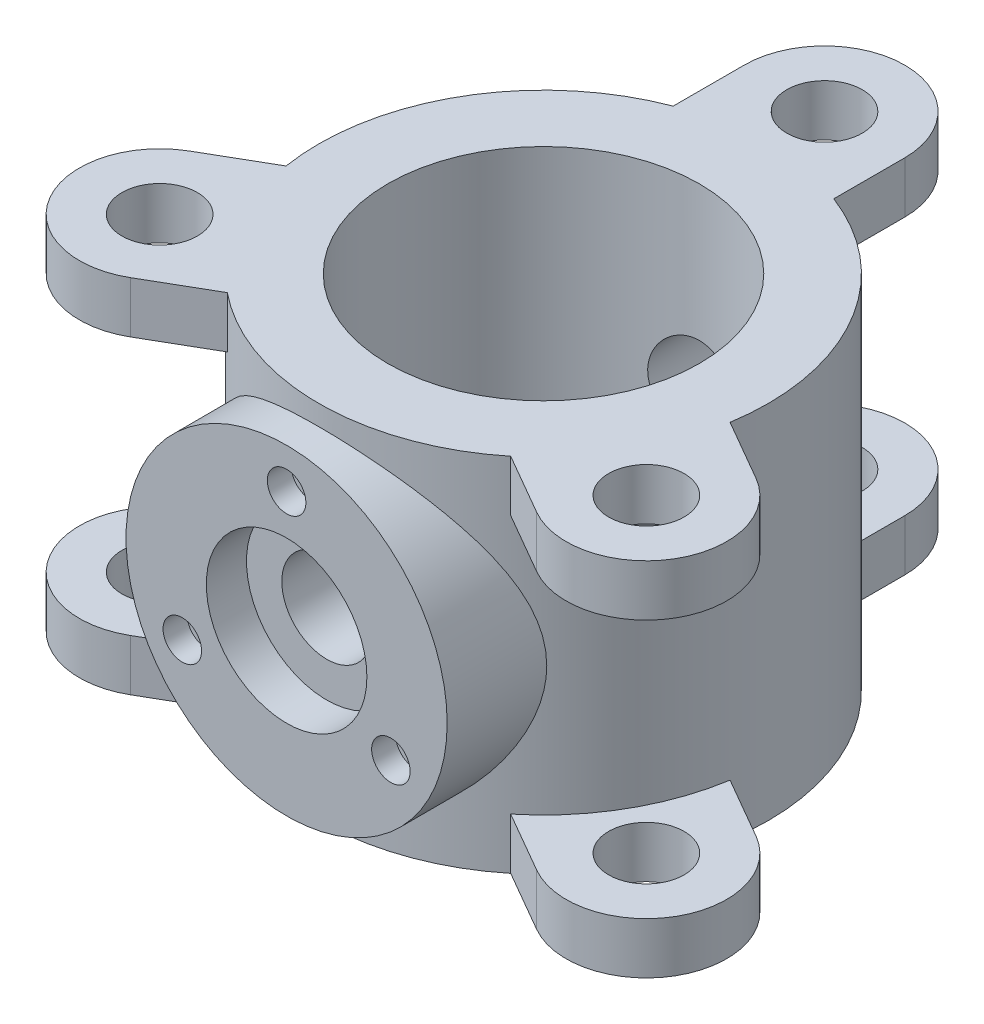
SolidWorks part; units mm, degrees
ref_plane "Front Plane" through (0, 0, 0) normal (0, 0, 1) x (1, 0, 0)
ref_plane "Top Plane" through (0, 0, 0) normal (0, 1, 0) x (1, 0, 0)
ref_plane "Right Plane" through (0, 0, 0) normal (1, 0, 0) x (0, 0, -1)
sketch "Sketch1" plane through (0, 0, 0) normal (0, 1, 0) x (1, 0, 0)
  circle A0 centre (0, 0) radius 140
  circle A1 centre (0, 0) radius 97
  dimension "D1" = 194
  dimension "D2" = 280
extrude "Boss-Extrude1" add sketch "Sketch1" along normal blind 225
sketch "Sketch3" plane through (0, 225, 0) normal (0, 1, 0) x (1, 0, 0)
  line L1 (50, 175) -> (-50, 175) construction
  line L2 (50, 175) -> (50, 101.9872)
  line L3 (50, 101.9872) -> (-50, 101.9872)
  line L4 (-50, 175) -> (-50, 101.9872)
  line L5 (50, 175) -> (-50, 101.9872) construction
  line L6 (50, 101.9872) -> (-50, 175) construction
  arc A0 (50, 175) -> (-50, 175) centre (0, 175) ccw
  circle A1 centre (0, 175) radius 23.5
  point P0 (0, 138.4936)
  dimension "D1" = 175
  dimension "D2" = 100
  dimension "D3" = 47
extrude "Boss-Extrude2" add sketch "Sketch3" against normal blind 32
pattern_circular "CirPattern1" count 3 over 360 about axis through (0, 0, 0) along (0, 1, 0) of "Boss-Extrude2"
ref_plane "Plane1" through (0, 112.5, 0) normal (0, 1, 0) x (1, 0, 0)
mirror "Mirror1" about plane through (0, 112.5, 0) normal (0, 1, 0) of "CirPattern1", "Boss-Extrude2"
ref_plane "Plane2" through (0, 0, 160) normal (0, 0, 1) x (1, 0, 0)
sketch "Sketch4" plane through (0, 0, 160) normal (0, 0, 1) x (1, 0, 0)
  line L0 (-88.2475, 0) -> (88.2475, 0) construction
  circle A0 centre (0, 112.5) radius 100
  dimension "D1" = 200
  dimension "D2" = 112.5
extrude "Boss-Extrude3" add sketch "Sketch4" against normal up to next
sketch "Sketch5" plane through (0, 0, 160) normal (0, 0, 1) x (1, 0, 0)
  circle A0 centre (0, 112.5) radius 50
  dimension "D1" = 100
extrude "Cut-Extrude1" cut sketch "Sketch5" against normal blind 25
sketch "Sketch6" plane through (0, 0, 135) normal (0, 0, 1) x (1, 0, 0)
  circle A0 centre (0, 112.5) radius 28
  dimension "D1" = 56
extrude "Cut-Extrude2" cut sketch "Sketch6" against normal through all
sketch "Sketch7" plane through (0, 0, 160) normal (0, 0, 1) x (1, 0, 0)
  circle A0 centre (0, 187.5) radius 12
  circle A1 centre (0, 112.5) radius 50 construction
  dimension "D1" = 24
  dimension "D2" = 75
extrude "Cut-Extrude3" cut sketch "Sketch7" against normal blind 15
pattern_circular "CirPattern2" count 3 over 360 about axis through (0, 112.5, 0) along (0, 0, 1) of "Cut-Extrude3"
